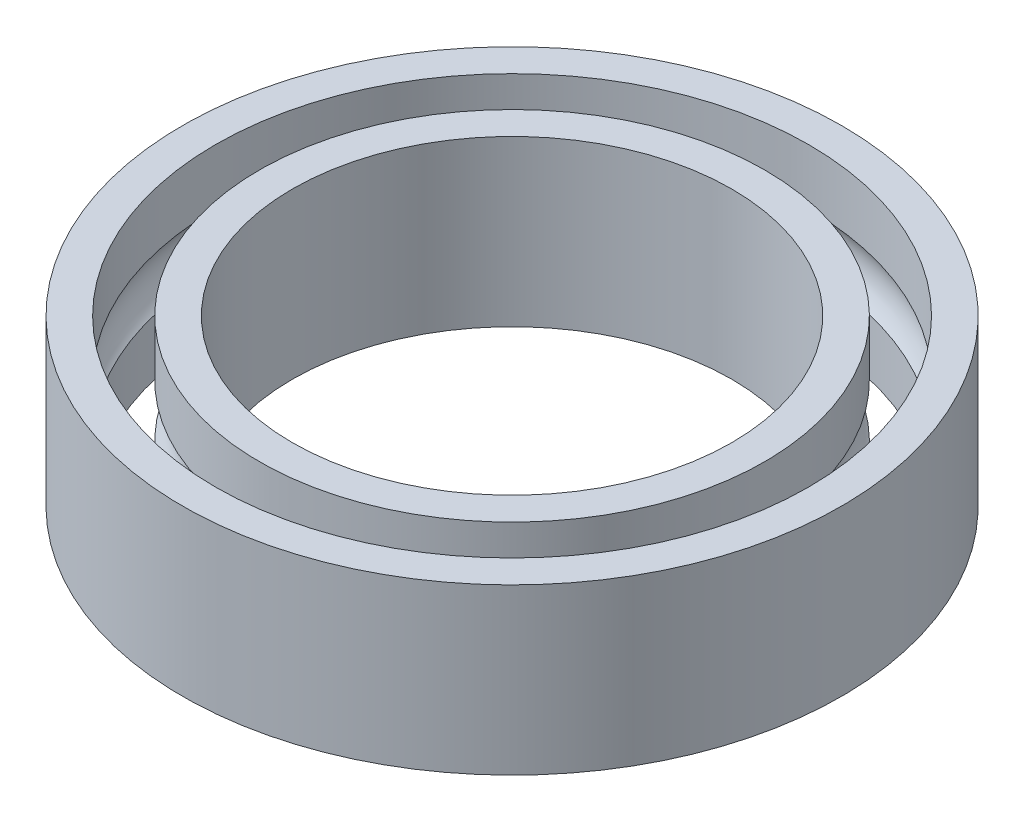
SolidWorks part; units mm, degrees
material "1.4511 (X3CrNb17)"
ref_plane "前视基准面" through (0, 0, 0) normal (0, 0, 1) x (1, 0, 0)
ref_plane "上视基准面" through (0, 0, 0) normal (0, 1, 0) x (1, 0, 0)
ref_plane "右视基准面" through (0, 0, 0) normal (1, 0, 0) x (0, 0, -1)
sketch "草图1" plane through (0, 0, 0) normal (0, 0, 1) x (1, 0, 0)
  line L0 (0, -7.417) -> (0, 7.417) construction
  line L1 (4, 1.5) -> (4.6, 1.5)
  line L2 (4, 1.5) -> (4, -1.5)
  line L3 (4, -1.5) -> (4.6, -1.5)
  line L4 (6, 1.5) -> (6, -1.5)
  line L5 (4, 1.5) -> (6, -1.5) construction
  line L6 (4, -1.5) -> (6, 1.5) construction
  line L7 (4.6, -1.5) -> (4.6, -0.4802)
  line L8 (5.4, -1.5) -> (5.4, -0.4802)
  line L9 (5.4, 1.5) -> (6, 1.5)
  line L10 (5.4, -1.5) -> (6, -1.5)
  line L11 (5.4, 0.4802) -> (5.4, 1.5)
  line L12 (4.6, 0.4802) -> (4.6, 1.5)
  arc A0 (4.6, 0.4802) -> (4.6, -0.4802) centre (5, 0) ccw
  arc A1 (5.4, -0.4802) -> (5.4, 0.4802) centre (5, 0) ccw
  point P0 (5, 0)
  point P9 (0, 0)
  dimension "D4" = 1.25
  dimension "D1" = 3
  dimension "D2" = 2
  dimension "D3" = 4
  dimension "D5" = 0.6
  dimension "D6" = 0.6
revolve "旋转1" add sketch "草图1" angle 360 about L0
